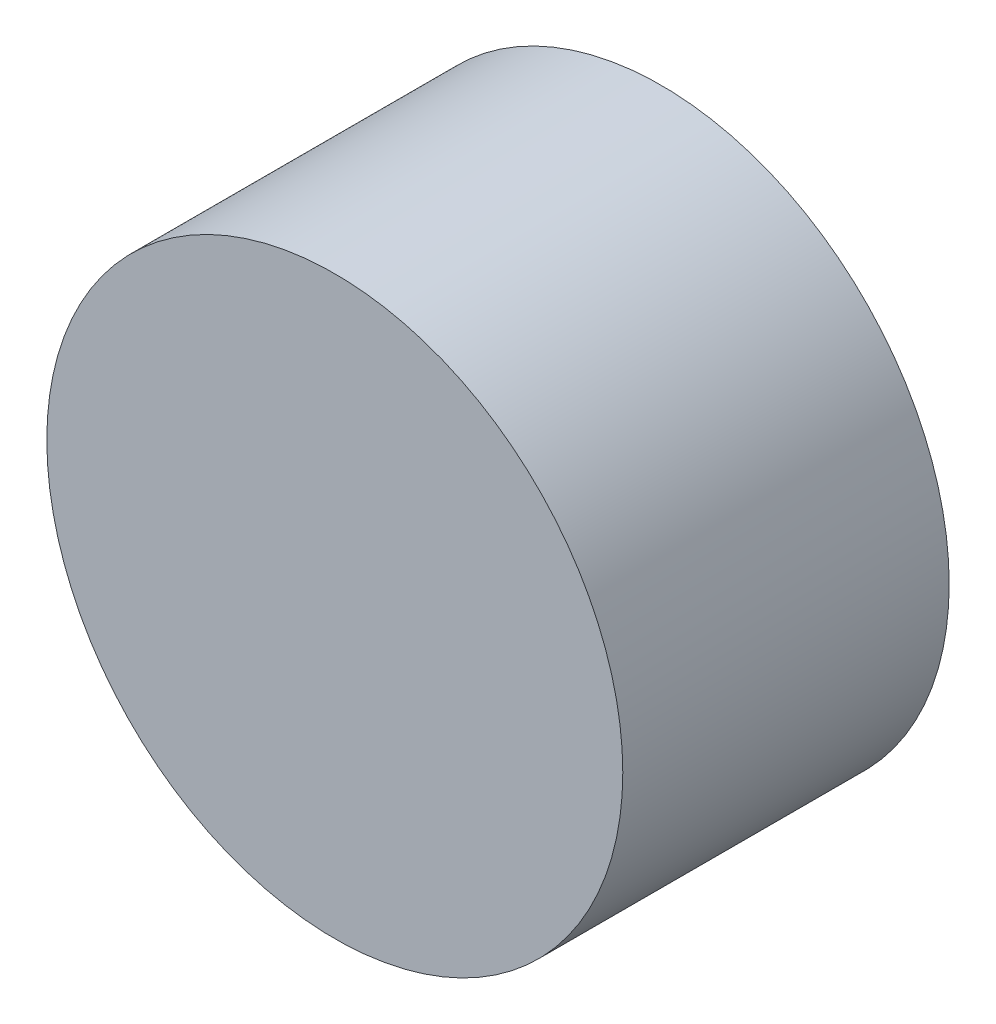
SolidWorks part; units mm, degrees
material "Alloy Steel"
ref_plane "Front Plane" through (0, 0, 0) normal (0, 0, 1) x (1, 0, 0)
ref_plane "Top Plane" through (0, 0, 0) normal (0, 1, 0) x (1, 0, 0)
ref_plane "Right Plane" through (0, 0, 0) normal (1, 0, 0) x (0, 0, -1)
sketch "Sketch1" plane through (0, 0, 0) normal (0, 0, 1) x (1, 0, 0)
  circle A0 centre (0, 0) radius 3
  dimension "D1" = 6
extrude "Boss-Extrude1" add sketch "Sketch1" along normal blind 3.4
